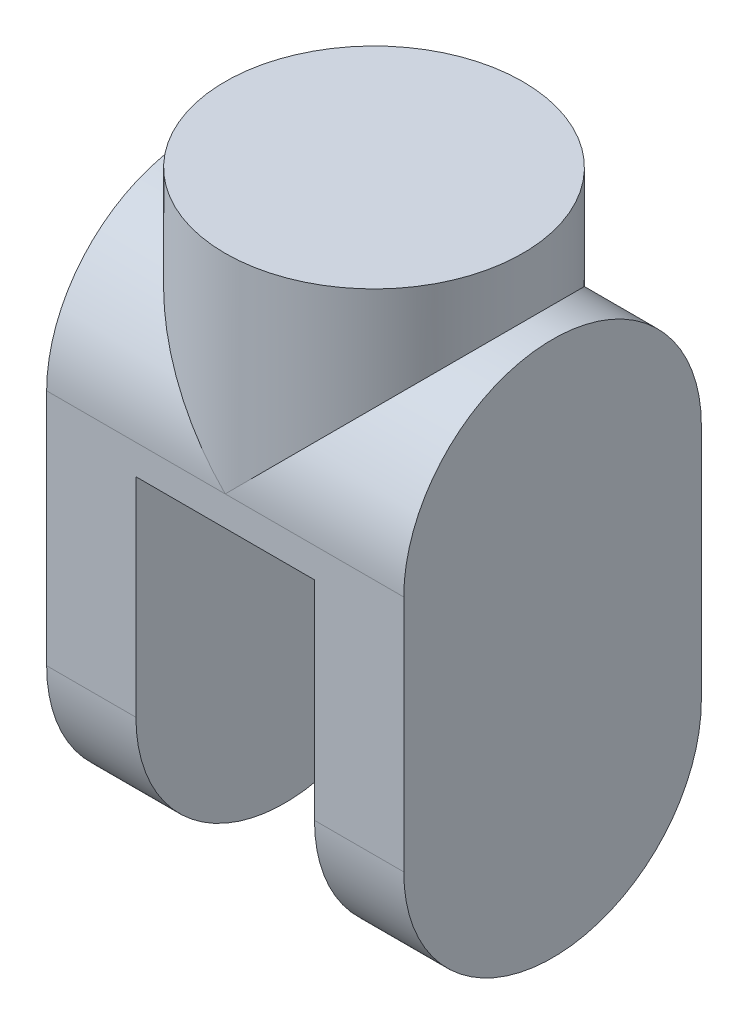
SolidWorks part; units mm, degrees
material "ABS"
ref_plane "Alzado" through (0, 0, 0) normal (0, 0, 1) x (1, 0, 0)
ref_plane "Planta" through (0, 0, 0) normal (0, 1, 0) x (1, 0, 0)
ref_plane "Vista lateral" through (0, 0, 0) normal (1, 0, 0) x (0, 0, -1)
sketch "Croquis1" plane through (0, 0, 0) normal (1, 0, 0) x (0, 0, -1)
  line L0 (-50, 80) -> (-50, 0)
  line L1 (50, 0) -> (50, 80)
  arc A0 (-50, 0) -> (50, 0) centre (0, 0) ccw
  arc A1 (50, 80) -> (-50, 80) centre (0, 80) ccw
  dimension "D1" = 80
  dimension "D2" = 100
extrude "Saliente-Extruir1" add sketch "Croquis1" along normal mid plane 120
sketch "Croquis2" plane through (0, 0, 0) normal (1, 0, 0) x (0, 0, -1)
  line L1 (-50, 70) -> (50, 70)
  line L2 (-50, 80) -> (-50, 0) construction
  line L3 (50, 0) -> (50, 80) construction
  line L5 (-50, 70) -> (-50, 0)
  line L7 (50, 70) -> (50, 0)
  arc A1 (-50, 0) -> (50, 0) centre (0, 0) ccw
  dimension "D1" = 70
extrude "Cortar-Extruir1" cut sketch "Croquis2" against normal mid plane 60
ref_plane "Plano1" through (0, 150, 0) normal (0, 1, 0) x (1, 0, 0)
sketch "Croquis3" plane through (0, 150, 0) normal (0, 1, 0) x (1, 0, 0)
  circle A0 centre (0, 0) radius 50
  dimension "D1" = 100
extrude "Saliente-Extruir2" add sketch "Croquis3" against normal up to next
